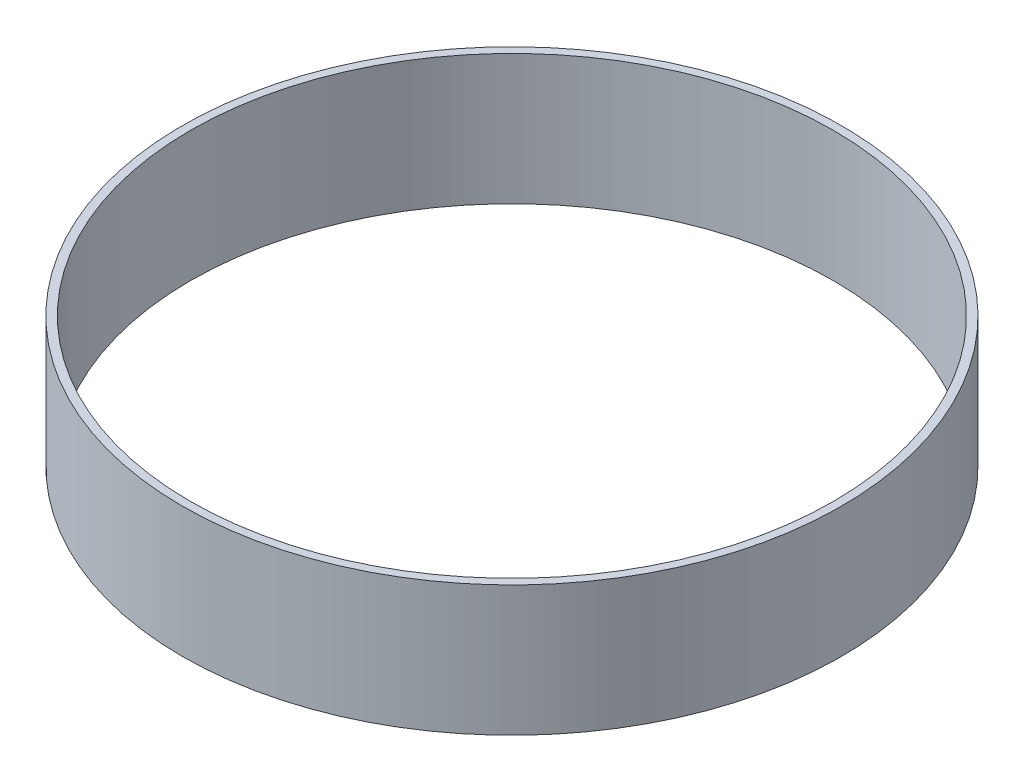
SolidWorks part; units mm, degrees
ref_plane "Front Plane" through (0, 0, 0) normal (0, 0, 1) x (1, 0, 0)
ref_plane "Top Plane" through (0, 0, 0) normal (0, 1, 0) x (1, 0, 0)
ref_plane "Right Plane" through (0, 0, 0) normal (1, 0, 0) x (0, 0, -1)
sketch "Sketch1" plane through (0, 0, 0) normal (0, 1, 0) x (1, 0, 0)
  circle A0 centre (0, 0) radius 40.5
  circle A1 centre (0, 0) radius 39.5
  dimension "D1" = 81
  dimension "D2" = 1
extrude "Boss-Extrude1" add sketch "Sketch1" along normal blind 16
